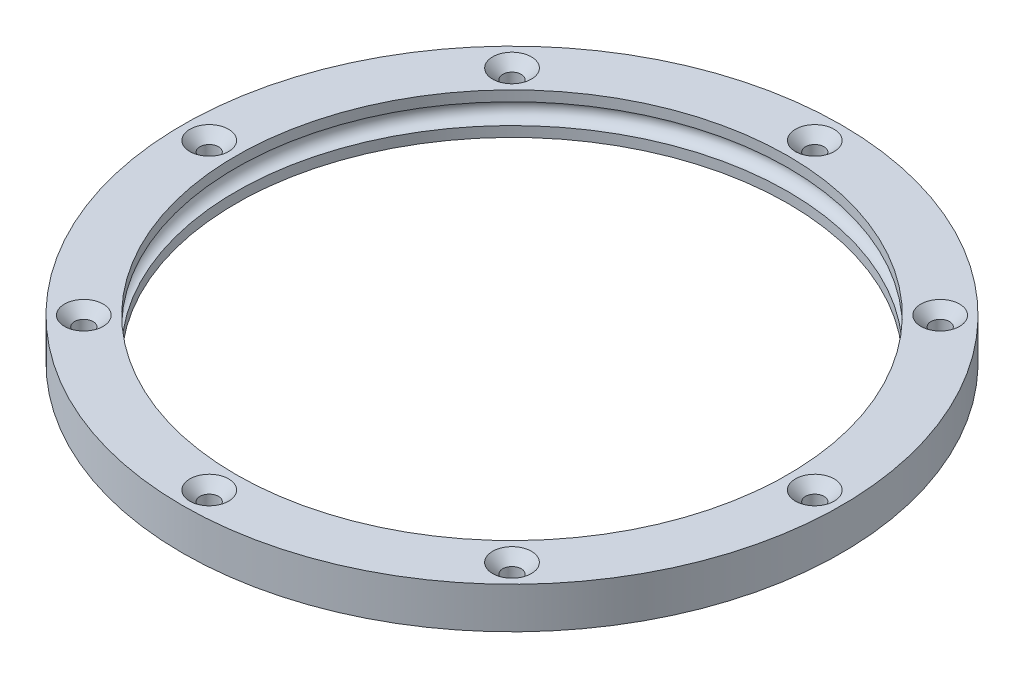
SolidWorks part; units mm, degrees
material "3003 Alloy"
ref_plane "Płaszczyzna przednia" through (0, 0, 0) normal (0, 0, 1) x (1, 0, 0)
ref_plane "Płaszczyzna górna" through (0, 0, 0) normal (0, 1, 0) x (1, 0, 0)
ref_plane "Płaszczyzna prawa" through (0, 0, 0) normal (1, 0, 0) x (0, 0, -1)
ref_axis "Axis1" through (0, -5.61, 0) along (0, 1, 0)
sketch "Sketch1" plane through (0, 0, 0) normal (0, 0, 1) x (1, 0, 0)
  line L0 (-67, -2.5) -> (-67, -5)
  line L1 (-67, 5) -> (-80, 5)
  line L2 (-67, 5) -> (-67, 2.5)
  line L3 (-67, -5) -> (-80, -5)
  line L4 (-80, 5) -> (-80, -5)
  line L5 (-67, 5) -> (-80, -5) construction
  line L6 (-67, -5) -> (-80, 5) construction
  arc A0 (-67, 2.5) -> (-67, -2.5) centre (-67, 0) ccw
  point P0 (-73.5, 0)
  dimension "D1" = 13
  dimension "D2" = 10
  dimension "D3" = 5
  dimension "D4" = 80
revolve "Revolve1" add sketch "Sketch1" angle 360 about axis through (0, -5.61, 0) along (0, 1, 0)
hole_wizard "CSK for M4 Countersunk Flat Head Screw1" positions "Sketch2" profile "Sketch4" countersink size "M4" standard "ISO" end condition through all
sketch "Sketch2" plane through (0, 5, 0) normal (0, 1, 0) x (1, 0, 0)
  point P0 (-73.5, 0)
sketch "Sketch4" plane through (-73.5, 5, 0) normal (1, 0, 0) x (0, 0, 1)
  line L0 (0, 0) -> (0, 10)
  line L1 (0, 10) -> (2.25, 10)
  line L2 (2.25, 10) -> (2.25, 2.45)
  line L3 (2.25, 2.45) -> (4.7, 0)
  line L5 (4.7, 0) -> (0, 0)
  line L6 (-2.25, 2.45) -> (-4.7, 0) construction
  line L11 (0, -6.35) -> (0, 107.95) construction
  dimension "Thru Hole Dia." = 4.5
  dimension "Thru Hole Depth" = 10
  dimension "Near C'Sink Dia." = 9.4
  dimension "Near C'Sink Angle" = 90
pattern_circular "CirPattern1" count 8 over 360 about axis through (0, 0, 0) along (0, 1, 0) of "CSK for M4 Countersunk Flat Head Screw1"
